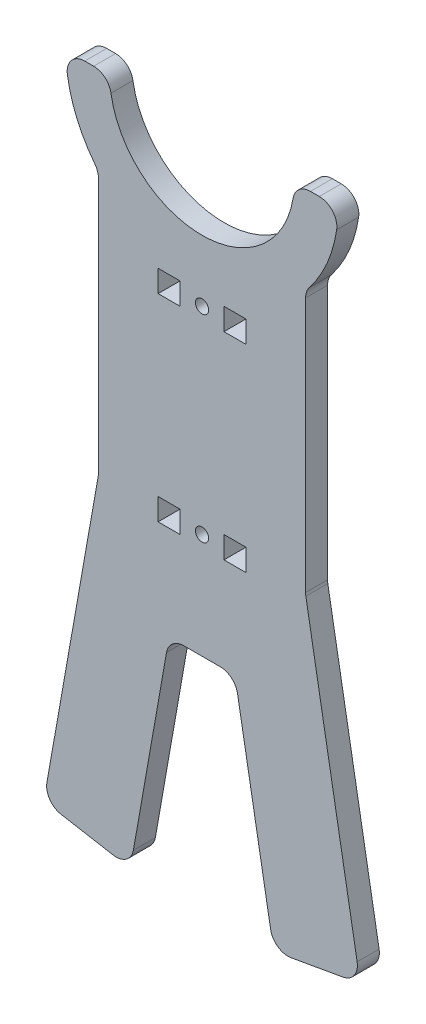
SolidWorks part; units mm, degrees
ref_plane "Front Plane" through (0, 0, 0) normal (0, 0, 1) x (1, 0, 0)
ref_plane "Top Plane" through (0, 0, 0) normal (0, 1, 0) x (1, 0, 0)
ref_plane "Right Plane" through (0, 0, 0) normal (1, 0, 0) x (0, 0, -1)
sketch "Sketch1" plane through (0, 0, 0) normal (0, 0, 1) x (1, 0, 0)
  line L0 (0, 0) -> (0, 60.0775) construction
  line L1 (0, 0) -> (83.5659, 0) construction
  line L2 (-21, 80) -> (-31, 80)
  line L3 (21, 80) -> (31, 80)
  line L4 (-23.5767, 59.8719) -> (-23.5767, 0)
  line L5 (-23.5767, 0) -> (-36.0125, -70.527)
  line L6 (-36.0125, -70.527) -> (-16.3163, -74)
  line L7 (-16.3163, -74) -> (-7.5, -24)
  line L8 (-7.5, -24) -> (7.5, -24)
  line L9 (7.5, -24) -> (16.3163, -74)
  line L10 (16.3163, -74) -> (36.0125, -70.527)
  line L11 (36.0125, -70.527) -> (23.5767, 0)
  line L12 (23.5767, 0) -> (23.5767, 59.8719)
  arc A0 (-21, 80) -> (21, 80) centre (0, 80) ccw
  arc A1 (23.5767, 59.8719) -> (31, 80) centre (0, 80) ccw
  arc A2 (-31, 80) -> (-23.5767, 59.8719) centre (0, 80) ccw
  line B0 (-5, 2.5) -> (-10, 2.5)
  line B1 (-5, 2.5) -> (-5, -2.5)
  line B2 (-5, -2.5) -> (-10, -2.5)
  line B3 (-10, 2.5) -> (-10, -2.5)
  line B4 (5, 2.5) -> (10, 2.5)
  line B5 (5, 2.5) -> (5, -2.5)
  line B6 (5, -2.5) -> (10, -2.5)
  line B7 (10, 2.5) -> (10, -2.5)
  circle B8 centre (0, 0) radius 1.5
  line B9 (-5, 47.5) -> (-10, 47.5)
  line B10 (-5, 47.5) -> (-5, 42.5)
  line B11 (-5, 42.5) -> (-10, 42.5)
  line B12 (-10, 47.5) -> (-10, 42.5)
  line B13 (5, 47.5) -> (10, 47.5)
  line B14 (5, 47.5) -> (5, 42.5)
  line B15 (5, 42.5) -> (10, 42.5)
  line B16 (10, 47.5) -> (10, 42.5)
  circle B17 centre (0, 45) radius 1.5
  dimension "D1" = 42
  dimension "D2" = 62
  dimension "D3" = 80
  dimension "D4" = 15
  dimension "D5" = 24
  dimension "D6" = 20
  dimension "D7" = 50
  dimension "D8" = 20
  dimension "D9" = 35
sketch_block_instance "Trou M3 plots 5mm-1"
sketch_block "Trou M3 plots 5mm" parameters "D2"=3, "D1"=5, "D3"=5, "D4"=10
sketch_block_instance "Trou M3 plots 5mm-3"
extrude "Boss-Extrude1" add sketch "Sketch1" along normal blind 5
fillet "Fillet1" radius 4 14 edges at (23.5767, 59.8719, 2.5) (-23.5767, 59.8719, 2.5) (-23.5767, 0, 2.5) (23.5767, 0, 2.5) (-36.0125, -70.527, 2.5) (-16.3163, -74, 2.5) (16.3163, -74, 2.5) (36.0125, -70.527, 2.5) (7.5, -24, 2.5) (-7.5, -24, 2.5) (31, 80, 2.5) (21, 80, 2.5) (-31, 80, 2.5) (-21, 80, 2.5)
